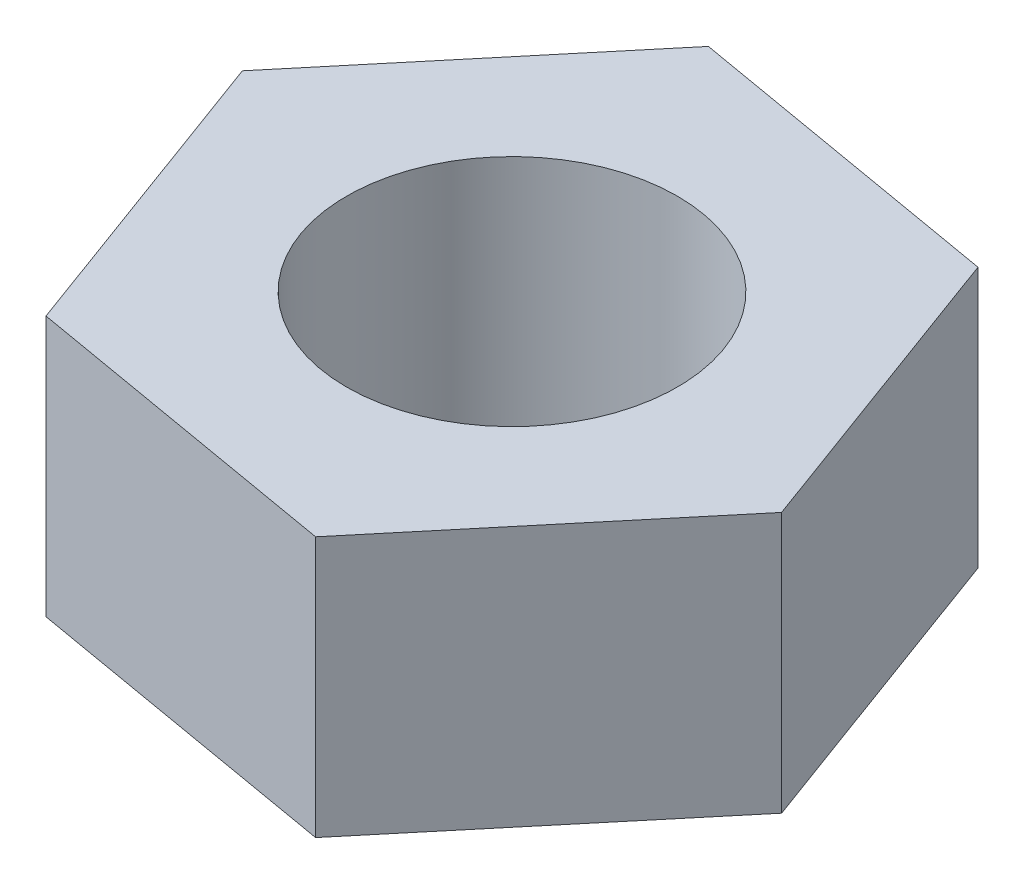
SolidWorks part; units mm, degrees
ref_plane "Front" through (0, 0, 0) normal (0, 0, 1) x (1, 0, 0)
ref_plane "Top" through (0, 0, 0) normal (0, 1, 0) x (1, 0, 0)
ref_plane "Right" through (0, 0, 0) normal (1, 0, 0) x (0, 0, -1)
sketch "Sketch1" plane through (0, 0, 0) normal (0, 1, 0) x (1, 0, 0)
  line L1 (-6.2579, 1.0829) -> (-4.0667, -4.878)
  line L2 (-4.0667, -4.878) -> (2.1911, -5.9609)
  line L3 (2.1911, -5.9609) -> (6.2579, -1.0829)
  line L4 (6.2579, -1.0829) -> (4.0667, 4.878)
  line L5 (4.0667, 4.878) -> (-2.1911, 5.9609)
  line L6 (-2.1911, 5.9609) -> (-6.2579, 1.0829)
  circle A0 centre (0, 0) radius 3.175
  circle A1 centre (0, 0) radius 5.5 construction
  dimension "D1" = 6.35
  dimension "D2" = 11
extrude "Boss-Extrude1" add sketch "Sketch1" along normal blind 5
